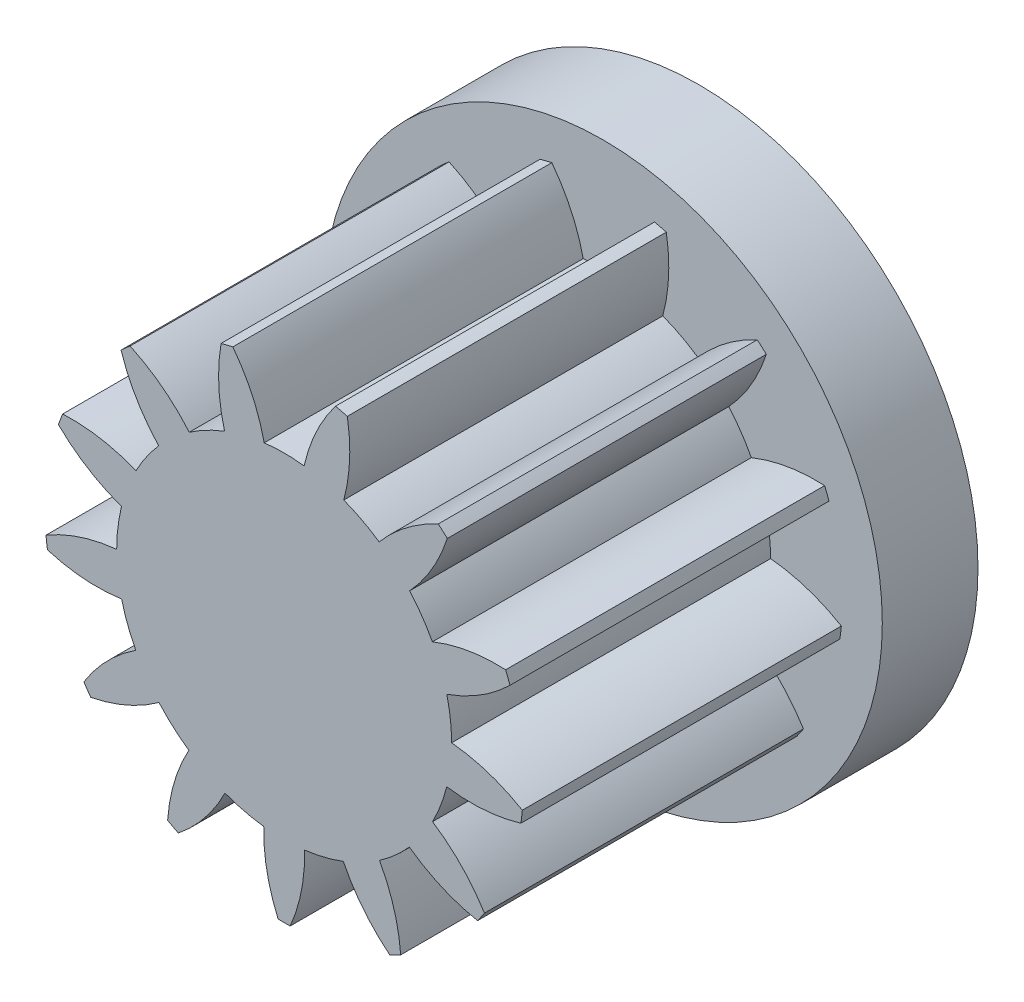
SolidWorks part; units mm, degrees
ref_plane "Front Plane" through (0, 0, 0) normal (0, 0, 1) x (1, 0, 0)
ref_plane "Top Plane" through (0, 0, 0) normal (0, 1, 0) x (1, 0, 0)
ref_plane "Right Plane" through (0, 0, 0) normal (1, 0, 0) x (0, 0, -1)
sketch "Sketch1" plane through (0, 0, 0) normal (0, 0, 1) x (1, 0, 0)
  circle A0 centre (0, 0) radius 8.75
  dimension "D1" = 17.5
extrude "Boss-Extrude1" add sketch "Sketch1" along normal blind 3
sketch "Sketch2" plane through (0, 0, 3) normal (0, 0, 1) x (1, 0, 0)
  line L0 (0, 13.3499) -> (0, -11.1917) construction
  line L1 (-11.7926, 0) -> (-5.25, 0) construction
  line L2 (0, 0) -> (2.575, 10.4442) construction
  line L3 (0, 0) -> (1.8688, 4.9061) construction
  line L4 (0, 0) -> (3.9347, 3.4757) construction
  line L5 (0, 0) -> (10.798, 0) construction
  arc A0 (2.9767, 4.3246) -> (1.8688, 4.9061) centre (0, 0) ccw
  arc A1 (-6.9428, 2.8368) -> (-7.0776, 2.4815) centre (0, 0) ccw
  arc A2 (1.6103, 7.3251) -> (0.626, 5.2125) centre (5.8976, 4.0419) ccw
  arc A3 (1.9793, 7.2341) -> (1.8688, 4.9061) centre (-3.3428, 6.3201) cw
  arc A4 (4.83, 5.7377) -> (2.9767, 4.3246) centre (7.1004, 0.8382) ccw
  arc A5 (5.1144, 5.4857) -> (3.9347, 3.4757) centre (-0.0228, 7.1497) cw
  arc A6 (6.9432, 2.8359) -> (4.6454, 2.4459) centre (6.6766, -2.5575) ccw
  arc A7 (7.0779, 2.4806) -> (5.0993, 1.249) centre (3.3024, 6.3413) cw
  arc A8 (7.4658, -0.7156) -> (5.25, 0.0069) centre (4.7233, -5.3674) ccw
  arc A9 (7.42, -1.0928) -> (5.0956, -1.2638) centre (5.8711, 4.0803) cw
  arc A10 (6.2781, -4.1032) -> (4.6518, -2.4337) centre (1.6879, -6.9476) ccw
  arc A11 (6.0622, -4.4159) -> (3.9246, -3.4871) centre (7.0948, 0.8845) cw
  arc A12 (3.6521, -6.5507) -> (2.988, -4.3168) centre (-1.7341, -6.9362) ccw
  arc A13 (3.3156, -6.7273) -> (1.8546, -4.9115) centre (6.6931, -2.514) cw
  arc A14 (0.1895, -7.4976) -> (0.6397, -5.2109) centre (-4.7589, -5.3358) ccw
  arc A15 (-0.1905, -7.4976) -> (-0.6403, -5.2108) centre (4.7582, -5.3365) cw
  arc A16 (-3.3165, -6.7269) -> (-1.8552, -4.9113) centre (-6.6935, -2.5131) ccw
  arc A17 (-3.653, -6.5502) -> (-2.9886, -4.3164) centre (1.7332, -6.9364) cw
  arc A18 (-6.0628, -4.4151) -> (-3.9251, -3.4865) centre (-7.0947, 0.8854) ccw
  arc A19 (-6.2786, -4.1023) -> (-4.6522, -2.4331) centre (-1.6889, -6.9474) cw
  arc A20 (-7.4201, -1.0919) -> (-5.0958, -1.2631) centre (-5.8705, 4.081) ccw
  arc A21 (-7.4659, -0.7146) -> (-5.25, 0.0076) centre (-4.724, -5.3667) cw
  arc A22 (-7.0776, 2.4815) -> (-5.0991, 1.2497) centre (-3.3015, 6.3418) ccw
  arc A23 (-6.9428, 2.8368) -> (-4.6451, 2.4465) centre (-6.677, -2.5566) cw
  arc A24 (-5.1137, 5.4864) -> (-3.9342, 3.4762) centre (0.0238, 7.1497) ccw
  arc A25 (-4.8292, 5.7383) -> (-2.9761, 4.325) centre (-7.1003, 0.8391) cw
  arc A26 (-1.9783, 7.2344) -> (-1.8681, 4.9064) centre (3.3437, 6.3196) ccw
  arc A27 (-1.6093, 7.3253) -> (-0.6253, 5.2126) centre (-5.897, 4.0427) cw
  arc A28 (-7.4659, -0.7146) -> (-7.4201, -1.0919) centre (0, 0) ccw
  arc A29 (-6.2786, -4.1023) -> (-6.0628, -4.4151) centre (0, 0) ccw
  arc A30 (-3.653, -6.5502) -> (-3.3165, -6.7269) centre (0, 0) ccw
  arc A31 (-0.1905, -7.4976) -> (0.1895, -7.4976) centre (0, 0) ccw
  arc A32 (3.3156, -6.7273) -> (3.6521, -6.5507) centre (0, 0) ccw
  arc A33 (6.0622, -4.4159) -> (6.2781, -4.1032) centre (0, 0) ccw
  arc A34 (7.42, -1.0928) -> (7.4658, -0.7156) centre (0, 0) ccw
  arc A35 (7.0779, 2.4806) -> (6.9432, 2.8359) centre (0, 0) ccw
  arc A36 (5.1144, 5.4857) -> (4.83, 5.7377) centre (0, 0) ccw
  arc A37 (1.9793, 7.2341) -> (1.6103, 7.3251) centre (0, 0) ccw
  arc A38 (-1.6093, 7.3253) -> (-1.9783, 7.2344) centre (0, 0) ccw
  arc A39 (-4.8292, 5.7383) -> (-5.1137, 5.4864) centre (0, 0) ccw
  arc A40 (0.626, 5.2125) -> (-0.6253, 5.2126) centre (0, 0) ccw
  arc A41 (-1.8681, 4.9064) -> (-2.9761, 4.325) centre (0, 0) ccw
  arc A42 (-3.9342, 3.4762) -> (-4.6451, 2.4465) centre (0, 0) ccw
  arc A43 (-5.0991, 1.2497) -> (-5.25, 0.0076) centre (0, 0) ccw
  arc A44 (-5.0958, -1.2631) -> (-4.6522, -2.4331) centre (0, 0) ccw
  arc A45 (-3.9251, -3.4865) -> (-2.9886, -4.3164) centre (0, 0) ccw
  arc A46 (-1.8552, -4.9113) -> (-0.6403, -5.2108) centre (0, 0) ccw
  arc A47 (0.6397, -5.2109) -> (1.8546, -4.9115) centre (0, 0) ccw
  arc A48 (2.988, -4.3168) -> (3.9246, -3.4871) centre (0, 0) ccw
  arc A49 (4.6518, -2.4337) -> (5.0956, -1.2638) centre (0, 0) ccw
  arc A50 (5.25, 0) -> (5.0993, 1.249) centre (0, 0) ccw
  arc A51 (4.6454, 2.4459) -> (3.9347, 3.4757) centre (0, 0) ccw
  dimension "D1" = 10.5
  dimension "D2" = 15
  dimension "D3" = 13.85
  dimension "D6" = 5.4
  dimension "D4" = 0.38
  dimension "D5" = 1.28
  dimension "D7" = 13
  dimension "D8" = 27.692
extrude "Boss-Extrude2" add sketch "Sketch2" along normal blind 10
